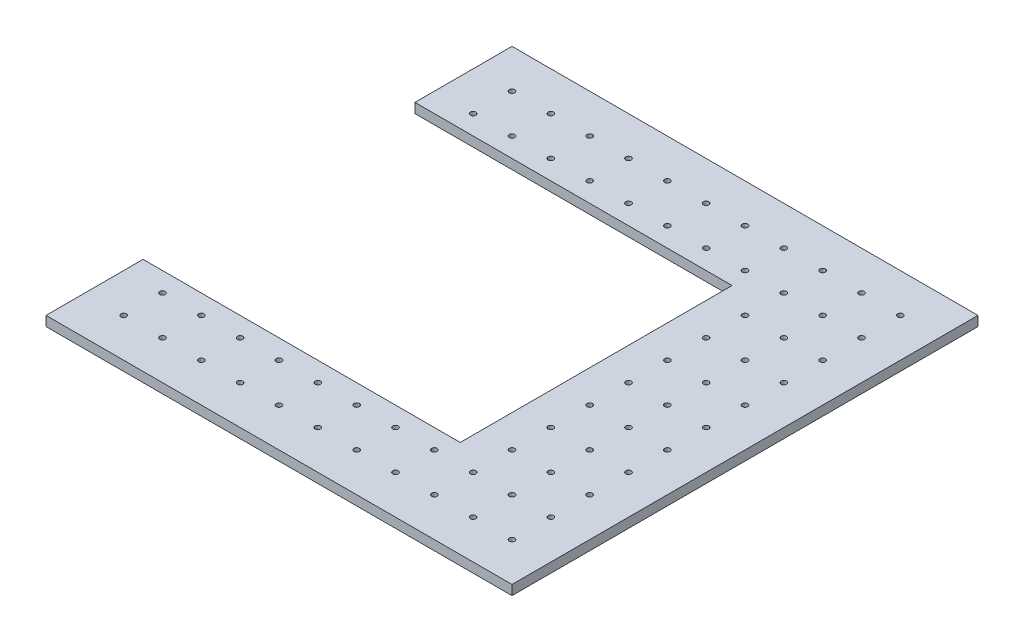
SolidWorks part; units mm, degrees
ref_plane "Front Plane" through (0, 0, 0) normal (0, 0, 1) x (1, 0, 0)
ref_plane "Top Plane" through (0, 0, 0) normal (0, 1, 0) x (1, 0, 0)
ref_plane "Right Plane" through (0, 0, 0) normal (1, 0, 0) x (0, 0, -1)
sketch "Sketch1" plane through (0, 0, 0) normal (0, 1, 0) x (1, 0, 0)
  line L0 (-65.2925, -101.6) -> (-39.8925, -101.6)
  line L1 (-97.0425, 152.4) -> (-97.0425, 127)
  line L2 (-97.0425, 203.2) -> (-97.0425, 177.8)
  line L3 (-90.6925, -107.95) -> (-65.2925, -107.95)
  line L4 (188.7075, 209.55) -> (214.1075, 209.55)
  line L5 (-90.6925, 177.8) -> (-90.6925, 152.4)
  line L6 (-97.0425, 203.2) -> (-65.2925, 203.2)
  line L7 (214.1075, 209.55) -> (214.1075, 177.8)
  line L8 (-65.2925, 209.55) -> (-65.2925, 203.2)
  line L9 (-39.8925, 209.55) -> (-39.8925, 203.2)
  line L10 (-14.4925, 209.55) -> (-14.4925, 203.2)
  line L11 (36.3075, 209.55) -> (36.3075, 203.2)
  line L12 (61.7075, 209.55) -> (61.7075, 203.2)
  line L13 (87.1075, 209.55) -> (87.1075, 203.2)
  line L14 (112.5075, 209.55) -> (112.5075, 203.2)
  line L15 (10.9075, 209.55) -> (10.9075, 203.2)
  line L16 (137.9075, 209.55) -> (137.9075, 203.2)
  line L17 (163.3075, 209.55) -> (163.3075, 203.2)
  line L18 (188.7075, 209.55) -> (188.7075, 203.2)
  line L19 (-97.0425, -76.2) -> (-90.6925, -76.2)
  line L20 (-97.0425, -50.8) -> (-90.6925, -50.8)
  line L21 (-97.0425, -25.4) -> (-90.6925, -25.4)
  line L22 (-97.0425, 0) -> (-90.6925, 0)
  line L23 (-97.0425, 25.4) -> (-90.6925, 25.4)
  line L24 (-97.0425, 50.8) -> (-90.6925, 50.8)
  line L25 (-97.0425, 76.2) -> (-90.6925, 76.2)
  line L26 (-97.0425, 101.6) -> (-90.6925, 101.6)
  line L27 (-97.0425, 127) -> (-90.6925, 127)
  line L28 (-97.0425, 152.4) -> (-90.6925, 152.4)
  line L29 (-97.0425, 177.8) -> (-90.6925, 177.8)
  line L30 (-39.8925, -107.95) -> (-14.4925, -107.95)
  line L31 (10.9075, -107.95) -> (36.3075, -107.95)
  line L32 (61.7075, -107.95) -> (87.1075, -107.95)
  line L33 (112.5075, -107.95) -> (137.9075, -107.95)
  line L34 (163.3075, -107.95) -> (188.7075, -107.95)
  line L35 (220.4575, -76.2) -> (220.4575, -101.6)
  line L36 (220.4575, -25.4) -> (220.4575, -50.8)
  line L37 (220.4575, 25.4) -> (220.4575, 0)
  line L38 (220.4575, 76.2) -> (220.4575, 50.8)
  line L39 (220.4575, 127) -> (220.4575, 101.6)
  line L40 (220.4575, 177.8) -> (220.4575, 152.4)
  line L41 (137.9075, 209.55) -> (163.3075, 209.55)
  line L42 (87.1075, 209.55) -> (112.5075, 209.55)
  line L43 (36.3075, 209.55) -> (61.7075, 209.55)
  line L44 (-14.4925, 209.55) -> (10.9075, 209.55)
  line L45 (-65.2925, 209.55) -> (-39.8925, 209.55)
  line L46 (-97.0425, 101.6) -> (-97.0425, 76.2)
  line L47 (-97.0425, 50.8) -> (-97.0425, 25.4)
  line L48 (-97.0425, 0) -> (-97.0425, -25.4)
  line L49 (-97.0425, -50.8) -> (-97.0425, -76.2)
  line L50 (-39.8925, 203.2) -> (-14.4925, 203.2)
  line L51 (10.9075, 203.2) -> (36.3075, 203.2)
  line L52 (61.7075, 203.2) -> (87.1075, 203.2)
  line L53 (112.5075, 203.2) -> (137.9075, 203.2)
  line L54 (163.3075, 203.2) -> (188.7075, 203.2)
  line L55 (214.1075, -76.2) -> (-90.6925, -76.2) construction
  line L56 (214.1075, -50.8) -> (-90.6925, -50.8) construction
  line L57 (-90.6925, -25.4) -> (214.1075, -25.4) construction
  line L58 (214.1075, 0) -> (-90.6925, 0) construction
  line L59 (-90.6925, 25.4) -> (214.1075, 25.4) construction
  line L60 (214.1075, 50.8) -> (-90.6925, 50.8) construction
  line L61 (-90.6925, 76.2) -> (214.1075, 76.2) construction
  line L62 (214.1075, 101.6) -> (-90.6925, 101.6) construction
  line L63 (-90.6925, 127) -> (214.1075, 127) construction
  line L64 (214.1075, 152.4) -> (-90.6925, 152.4) construction
  line L65 (-90.6925, 177.8) -> (214.1075, 177.8) construction
  line L66 (-90.6925, -76.2) -> (-90.6925, -107.95)
  line L67 (-90.6925, 127) -> (-90.6925, 101.6)
  line L68 (-90.6925, 76.2) -> (-90.6925, 50.8)
  line L69 (-90.6925, 25.4) -> (-90.6925, 0)
  line L70 (-90.6925, -25.4) -> (-90.6925, -50.8)
  line L71 (-14.4925, -101.6) -> (10.9075, -101.6)
  line L72 (36.3075, -101.6) -> (61.7075, -101.6)
  line L73 (87.1075, -101.6) -> (112.5075, -101.6)
  line L74 (137.9075, -101.6) -> (163.3075, -101.6)
  line L75 (188.7075, -101.6) -> (220.4575, -101.6)
  line L76 (214.1075, -50.8) -> (214.1075, -76.2)
  line L77 (214.1075, 0) -> (214.1075, -25.4)
  line L78 (214.1075, 50.8) -> (214.1075, 25.4)
  line L79 (214.1075, 76.2) -> (220.4575, 76.2)
  line L80 (214.1075, 101.6) -> (214.1075, 76.2)
  line L81 (214.1075, 152.4) -> (214.1075, 127)
  line L82 (214.1075, 177.8) -> (220.4575, 177.8)
  line L83 (214.1075, 152.4) -> (220.4575, 152.4)
  line L84 (214.1075, 127) -> (220.4575, 127)
  line L85 (214.1075, 101.6) -> (220.4575, 101.6)
  line L86 (214.1075, 50.8) -> (220.4575, 50.8)
  line L87 (214.1075, 25.4) -> (220.4575, 25.4)
  line L88 (214.1075, 0) -> (220.4575, 0)
  line L89 (214.1075, -25.4) -> (220.4575, -25.4)
  line L90 (214.1075, -50.8) -> (220.4575, -50.8)
  line L91 (214.1075, -76.2) -> (220.4575, -76.2)
  line L92 (188.7075, -101.6) -> (188.7075, -107.95)
  line L93 (163.3075, -101.6) -> (163.3075, -107.95)
  line L94 (137.9075, -101.6) -> (137.9075, -107.95)
  line L95 (112.5075, -101.6) -> (112.5075, -107.95)
  line L96 (87.1075, -101.6) -> (87.1075, -107.95)
  line L97 (61.7075, -101.6) -> (61.7075, -107.95)
  line L98 (36.3075, -101.6) -> (36.3075, -107.95)
  line L99 (10.9075, -101.6) -> (10.9075, -107.95)
  line L100 (-14.4925, -101.6) -> (-14.4925, -107.95)
  line L101 (-39.8925, -101.6) -> (-39.8925, -107.95)
  line L102 (-65.2925, -101.6) -> (-65.2925, -107.95)
  line L103 (-65.2925, 203.2) -> (-65.2925, -101.6) construction
  line L104 (-39.8925, 203.2) -> (-39.8925, -101.6) construction
  line L105 (-14.4925, 203.2) -> (-14.4925, -101.6) construction
  line L106 (10.9075, 203.2) -> (10.9075, -101.6) construction
  line L107 (36.3075, 203.2) -> (36.3075, -101.6) construction
  line L108 (61.7075, 203.2) -> (61.7075, -101.6) construction
  line L109 (87.1075, -101.6) -> (87.1075, 203.2) construction
  line L110 (112.5075, 203.2) -> (112.5075, -101.6) construction
  line L111 (137.9075, 203.2) -> (137.9075, -101.6) construction
  line L112 (163.3075, 203.2) -> (163.3075, -101.6) construction
  line L113 (188.7075, 203.2) -> (188.7075, -101.6) construction
  line L114 (-65.2925, -76.2) -> (-39.8925, -76.2) construction
  line L115 (-65.2925, -76.2) -> (-65.2925, -50.8) construction
  line L116 (-65.2925, -50.8) -> (-39.8925, -50.8) construction
  circle A0 centre (-65.2925, -76.2) radius 1.7907
  circle A1 centre (-39.8925, -76.2) radius 1.7907
  circle A2 centre (-14.4925, -76.2) radius 1.7907
  circle A3 centre (10.9075, -76.2) radius 1.7907
  circle A4 centre (36.3075, -76.2) radius 1.7907
  circle A5 centre (61.7075, -76.2) radius 1.7907
  circle A6 centre (87.1075, -76.2) radius 1.7907
  circle A7 centre (112.5075, -76.2) radius 1.7907
  circle A8 centre (137.9075, -76.2) radius 1.7907
  circle A9 centre (163.3075, -76.2) radius 1.7907
  circle A10 centre (188.7075, -76.2) radius 1.7907
  circle A11 centre (-65.2925, -50.8) radius 1.7907
  circle A12 centre (-65.2925, -25.4) radius 1.7907
  circle A13 centre (-65.2925, 0) radius 1.7907
  circle A14 centre (-65.2925, 25.4) radius 1.7907
  circle A15 centre (-65.2925, 50.8) radius 1.7907
  circle A16 centre (-65.2925, 76.2) radius 1.7907
  circle A17 centre (-65.2925, 101.6) radius 1.7907
  circle A18 centre (-65.2925, 127) radius 1.7907
  circle A19 centre (-65.2925, 152.4) radius 1.7907
  circle A20 centre (-65.2925, 177.8) radius 1.7907
  circle A21 centre (-39.8925, -50.8) radius 1.7907
  circle A22 centre (-14.4925, -50.8) radius 1.7907
  circle A23 centre (10.9075, -50.8) radius 1.7907
  circle A24 centre (36.3075, -50.8) radius 1.7907
  circle A25 centre (61.7075, -50.8) radius 1.7907
  circle A26 centre (87.1075, -50.8) radius 1.7907
  circle A27 centre (112.5075, -50.8) radius 1.7907
  circle A28 centre (137.9075, -50.8) radius 1.7907
  circle A29 centre (163.3075, -50.8) radius 1.7907
  circle A30 centre (188.7075, -50.8) radius 1.7907
  circle A31 centre (-39.8925, -25.4) radius 1.7907
  circle A32 centre (-14.4925, -25.4) radius 1.7907
  circle A33 centre (10.9075, -25.4) radius 1.7907
  circle A34 centre (36.3075, -25.4) radius 1.7907
  circle A35 centre (61.7075, -25.4) radius 1.7907
  circle A36 centre (87.1075, -25.4) radius 1.7907
  circle A37 centre (112.5075, -25.4) radius 1.7907
  circle A38 centre (137.9075, -25.4) radius 1.7907
  circle A39 centre (163.3075, -25.4) radius 1.7907
  circle A40 centre (188.7075, -25.4) radius 1.7907
  circle A41 centre (-39.8925, 0) radius 1.7907
  circle A42 centre (-14.4925, 0) radius 1.7907
  circle A43 centre (10.9075, 0) radius 1.7907
  circle A44 centre (36.3075, 0) radius 1.7907
  circle A45 centre (61.7075, 0) radius 1.7907
  circle A46 centre (87.1075, 0) radius 1.7907
  circle A47 centre (112.5075, 0) radius 1.7907
  circle A48 centre (137.9075, 0) radius 1.7907
  circle A49 centre (163.3075, 0) radius 1.7907
  circle A50 centre (188.7075, 0) radius 1.7907
  circle A51 centre (-39.8925, 25.4) radius 1.7907
  circle A52 centre (-14.4925, 25.4) radius 1.7907
  circle A53 centre (10.9075, 25.4) radius 1.7907
  circle A54 centre (36.3075, 25.4) radius 1.7907
  circle A55 centre (61.7075, 25.4) radius 1.7907
  circle A56 centre (87.1075, 25.4) radius 1.7907
  circle A57 centre (112.5075, 25.4) radius 1.7907
  circle A58 centre (137.9075, 25.4) radius 1.7907
  circle A59 centre (163.3075, 25.4) radius 1.7907
  circle A60 centre (188.7075, 25.4) radius 1.7907
  circle A61 centre (-39.8925, 50.8) radius 1.7907
  circle A62 centre (-14.4925, 50.8) radius 1.7907
  circle A63 centre (10.9075, 50.8) radius 1.7907
  circle A64 centre (36.3075, 50.8) radius 1.7907
  circle A65 centre (61.7075, 50.8) radius 1.7907
  circle A66 centre (87.1075, 50.8) radius 1.7907
  circle A67 centre (112.5075, 50.8) radius 1.7907
  circle A68 centre (137.9075, 50.8) radius 1.7907
  circle A69 centre (163.3075, 50.8) radius 1.7907
  circle A70 centre (188.7075, 50.8) radius 1.7907
  circle A71 centre (-39.8925, 76.2) radius 1.7907
  circle A72 centre (-14.4925, 76.2) radius 1.7907
  circle A73 centre (10.9075, 76.2) radius 1.7907
  circle A74 centre (36.3075, 76.2) radius 1.7907
  circle A75 centre (61.7075, 76.2) radius 1.7907
  circle A76 centre (87.1075, 76.2) radius 1.7907
  circle A77 centre (112.5075, 76.2) radius 1.7907
  circle A78 centre (137.9075, 76.2) radius 1.7907
  circle A79 centre (163.3075, 76.2) radius 1.7907
  circle A80 centre (188.7075, 76.2) radius 1.7907
  circle A81 centre (-39.8925, 101.6) radius 1.7907
  circle A82 centre (-14.4925, 101.6) radius 1.7907
  circle A83 centre (10.9075, 101.6) radius 1.7907
  circle A84 centre (36.3075, 101.6) radius 1.7907
  circle A85 centre (61.7075, 101.6) radius 1.7907
  circle A86 centre (87.1075, 101.6) radius 1.7907
  circle A87 centre (112.5075, 101.6) radius 1.7907
  circle A88 centre (137.9075, 101.6) radius 1.7907
  circle A89 centre (163.3075, 101.6) radius 1.7907
  circle A90 centre (188.7075, 101.6) radius 1.7907
  circle A91 centre (-39.8925, 127) radius 1.7907
  circle A92 centre (-14.4925, 127) radius 1.7907
  circle A93 centre (10.9075, 127) radius 1.7907
  circle A94 centre (36.3075, 127) radius 1.7907
  circle A95 centre (61.7075, 127) radius 1.7907
  circle A96 centre (87.1075, 127) radius 1.7907
  circle A97 centre (112.5075, 127) radius 1.7907
  circle A98 centre (137.9075, 127) radius 1.7907
  circle A99 centre (163.3075, 127) radius 1.7907
  circle A100 centre (188.7075, 127) radius 1.7907
  circle A101 centre (-39.8925, 152.4) radius 1.7907
  circle A102 centre (-14.4925, 152.4) radius 1.7907
  circle A103 centre (10.9075, 152.4) radius 1.7907
  circle A104 centre (36.3075, 152.4) radius 1.7907
  circle A105 centre (61.7075, 152.4) radius 1.7907
  circle A106 centre (87.1075, 152.4) radius 1.7907
  circle A107 centre (112.5075, 152.4) radius 1.7907
  circle A108 centre (137.9075, 152.4) radius 1.7907
  circle A109 centre (163.3075, 152.4) radius 1.7907
  circle A110 centre (188.7075, 152.4) radius 1.7907
  circle A111 centre (-39.8925, 177.8) radius 1.7907
  circle A112 centre (-14.4925, 177.8) radius 1.7907
  circle A113 centre (10.9075, 177.8) radius 1.7907
  circle A114 centre (36.3075, 177.8) radius 1.7907
  circle A115 centre (61.7075, 177.8) radius 1.7907
  circle A116 centre (87.1075, 177.8) radius 1.7907
  circle A117 centre (112.5075, 177.8) radius 1.7907
  circle A118 centre (137.9075, 177.8) radius 1.7907
  circle A119 centre (163.3075, 177.8) radius 1.7907
  circle A120 centre (188.7075, 177.8) radius 1.7907
  dimension "D5" = 3.5814
  dimension "D6" = 25.4
  dimension "D3" = 6.35
  dimension "D4" = 6.35
  dimension "D7" = 25.4
  dimension "D8" = 50.8
  dimension "D9" = 76.2
  dimension "D10" = 101.6
  dimension "D11" = 127
  dimension "D12" = 152.4
  dimension "D13" = 177.8
  dimension "D14" = 203.2
  dimension "D15" = 228.6
  dimension "D16" = 254
  dimension "D17" = 279.4
  dimension "D18" = 25.4
  dimension "D19" = 50.8
  dimension "D20" = 76.2
  dimension "D21" = 101.6
  dimension "D22" = 127
  dimension "D23" = 152.4
  dimension "D24" = 177.8
  dimension "D25" = 203.2
  dimension "D26" = 228.6
  dimension "D27" = 254
  dimension "D28" = 279.4
  dimension "D29" = 304.8
  dimension "D31" = 25.4
  dimension "D33" = 25.4
  dimension "D35" = 25.4
  dimension "D30" = 11
  dimension "D32" = 11
  dimension "D34" = 11
  dimension "D36" = 11
  dimension "D37" = 11
  dimension "D38" = 11
  dimension "D39" = 11
  dimension "D40" = 11
  dimension "D41" = 11
  dimension "D42" = 11
  dimension "D43" = 11
  dimension "D44" = 11
extrude "Boss-Extrude1" add sketch "Sketch1" along normal blind 6.35
sketch "Sketch2" plane through (0, 6.35, 0) normal (0, 1, 0) x (1, 0, 0)
  line L0 (-90.6925, -25.4) -> (-90.6925, -50.8) construction
  line L1 (-137.2491, 139.7) -> (116.7509, 139.7)
  line L2 (-137.2491, 139.7) -> (-137.2491, -38.1)
  line L3 (-137.2491, -38.1) -> (116.7509, -38.1)
  line L4 (116.7509, 139.7) -> (116.7509, -38.1)
  line L5 (188.7075, -101.6) -> (220.4575, -101.6) construction
  line L6 (-97.0425, 203.2) -> (214.1075, 203.2)
  line L7 (-97.0425, 203.2) -> (-97.0425, 209.55)
  line L8 (-97.0425, 209.55) -> (214.1075, 209.55)
  line L9 (214.1075, 203.2) -> (214.1075, 209.55)
  line L10 (220.4575, 177.8) -> (214.1075, 177.8)
  line L11 (220.4575, 177.8) -> (220.4575, -101.6)
  line L12 (220.4575, -101.6) -> (214.1075, -101.6)
  line L13 (214.1075, 177.8) -> (214.1075, -101.6)
  line L14 (-90.6925, -76.2) -> (-90.6925, -107.95) construction
  line L15 (188.7075, -107.95) -> (-90.6925, -107.95)
  line L16 (188.7075, -107.95) -> (188.7075, -101.6)
  line L17 (188.7075, -101.6) -> (-90.6925, -101.6)
  line L18 (-90.6925, -107.95) -> (-90.6925, -101.6)
  circle A0 centre (-65.2925, -76.2) radius 1.7907 construction
  dimension "D1" = 177.8
  dimension "D2" = 254
  dimension "D3" = 38.1
  dimension "D4" = 46.5567
extrude "Cut-Extrude2" cut sketch "Sketch2" against normal through all
sketch "Sketch3" plane through (0, 6.35, 0) normal (0, 1, 0) x (1, 0, 0)
  line L0 (214.1075, 203.2) -> (-97.0425, 203.2) construction
  line L1 (-97.0425, 139.7) -> (-90.6925, 139.7)
  line L2 (-97.0425, 139.7) -> (-97.0425, 203.2)
  line L3 (-97.0425, 203.2) -> (-90.6925, 203.2)
  line L4 (-90.6925, 139.7) -> (-90.6925, 203.2)
  line L6 (-97.0425, -76.2) -> (-90.6925, -76.2)
  line L7 (-97.0425, -76.2) -> (-97.0425, -50.8)
  line L8 (-97.0425, -50.8) -> (-90.6925, -50.8)
  line L9 (-90.6925, -76.2) -> (-90.6925, -50.8)
extrude "Cut-Extrude3" cut sketch "Sketch3" against normal through all
